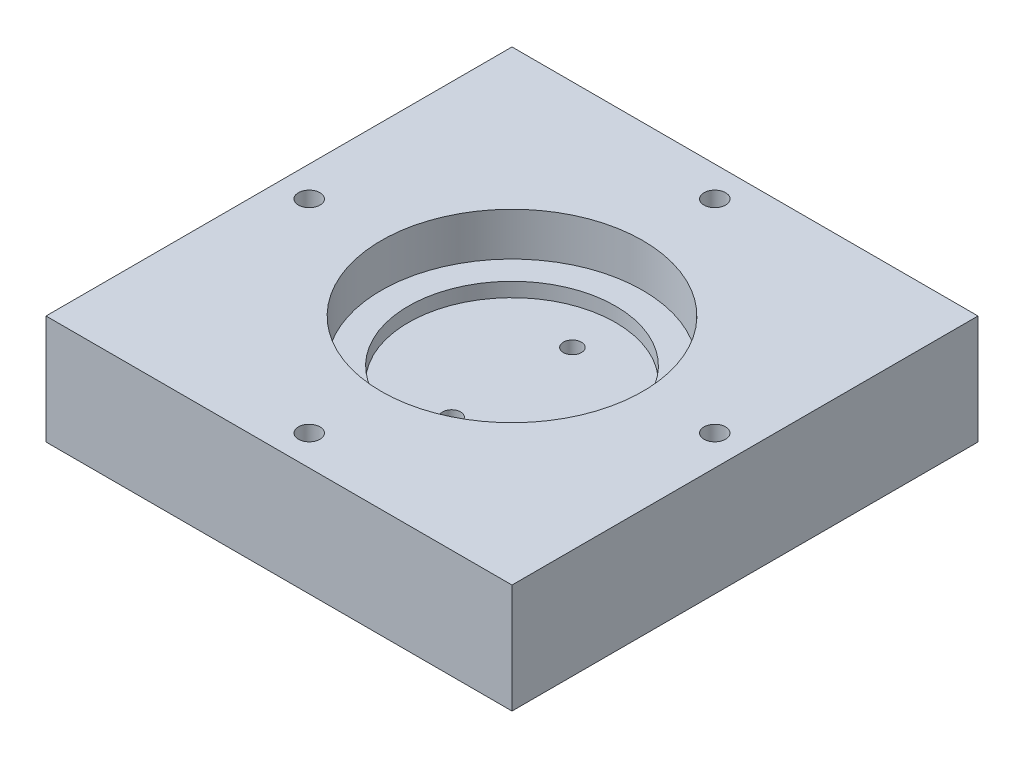
SolidWorks part; units mm, degrees
ref_plane "Front Plane" through (0, 0, 0) normal (0, 0, 1) x (1, 0, 0)
ref_plane "Top Plane" through (0, 0, 0) normal (0, 1, 0) x (1, 0, 0)
ref_plane "Right Plane" through (0, 0, 0) normal (1, 0, 0) x (0, 0, -1)
sketch "Sketch1" plane through (0, 0, 0) normal (0, 1, 0) x (1, 0, 0)
  circle A0 centre (0, 0) radius 11.5 construction
  circle A1 centre (0, 0) radius 7 construction
  circle A2 centre (0, 7) radius 1.05
  circle A3 centre (0, -7) radius 1.05
  circle A6 centre (0, 0) radius 27
  dimension "D1" = 23
  dimension "D2" = 2.1
  dimension "D3" = 14
  dimension "D4" = 54
extrude "Boss-Extrude1" add sketch "Sketch1" along normal blind 3
sketch "Sketch2" plane through (0, 3, 0) normal (0, 1, 0) x (1, 0, 0)
  circle A0 centre (0, 0) radius 12
  circle A1 centre (0, 0) radius 27
  dimension "D1" = 24
extrude "Boss-Extrude2" add sketch "Sketch2" along normal blind 1.65
sketch "Sketch3" plane through (0, 4.65, 0) normal (0, 1, 0) x (1, 0, 0)
  line L0 (-1.65, 0) -> (1.65, 0) construction
  line L1 (-26.971, 1.25) -> (-15.0983, 1.25) construction
  line L5 (-26.971, -1.25) -> (-15.0983, -1.25) construction
  arc A0 (-26.971, -1.25) -> (-26.971, 1.25) centre (0, 0) ccw construction
  circle A2 centre (0, 0) radius 27 construction
  arc A4 (-15.0983, -1.25) -> (-15.0983, 1.25) centre (0, 0) ccw construction
  circle A6 centre (0, 0) radius 15.15
  circle A7 centre (0, 0) radius 27
  dimension "D3" = 15.15
  dimension "D4" = 54
  dimension "D5" = 30.3
  dimension "D1" = 2.5
  dimension "D2" = 1.25
extrude "Boss-Extrude3" add sketch "Sketch3" along normal blind 5
fillet "Fillet1" [suppressed] radius 2.5
sketch "Sketch4" plane through (0, 0, 0) normal (0, -1, 0) x (1, 0, 0)
  circle A0 centre (0, -7) radius 1.875
  circle A1 centre (0, 7) radius 1.875
  circle A2 centre (0, 0) radius 27
  dimension "D1" = 3.75
  dimension "D2" = 3.75
extrude "Boss-Extrude4" add sketch "Sketch4" along normal blind 3
sketch "Sketch5" plane through (0, 9.65, 0) normal (0, 1, 0) x (1, 0, 0)
  line L5 (0, -1.65) -> (0, 1.65) construction
  line L6 (-0.75, 27.9703) -> (0.75, 27.9703)
  line L7 (-0.75, 27.9703) -> (-0.75, 24)
  line L8 (-0.75, 24) -> (0.75, 24)
  line L9 (0.75, 27.9703) -> (0.75, 24)
  circle A0 centre (0, 0) radius 27 construction
  point P4 (0, 27.9703)
  dimension "D2" = 3
  dimension "D1" = 1.5
extrude "Cut-Extrude1" [suppressed] cut sketch "Sketch5" against normal through all
pattern_circular "CirPattern1" [suppressed] count 8 over 360
sketch "Sketch6" plane through (0, 9.65, 0) normal (0, 1, 0) x (1, 0, 0)
  line L0 (0, -6.9575) -> (0, 6.9575) construction
  circle A0 centre (0, 23.5) radius 1.25
  dimension "D2" = 2.5
  dimension "D1" = 23.5
extrude "Cut-Extrude2" cut sketch "Sketch6" against normal through all
pattern_circular "CirPattern2" count 4 over 360 about axis through (0, 0, 0) along (0, 1, 0) of "Cut-Extrude2"
sketch "Sketch7" plane through (0, 0, 0) normal (0, 1, 0) x (1, 0, 0)
  line L1 (-27, 27) -> (27, 27)
  line L2 (-27, 27) -> (-27, -27)
  line L3 (-27, -27) -> (27, -27)
  line L4 (27, 27) -> (27, -27)
  circle A0 centre (0, 0) radius 27
extrude "Boss-Extrude5" add sketch "Sketch7" along normal up to surface and the other way up to surface contours A0 L1 L2 | A0 L4 L1 | A0 L3 L4 | A0 L2 L3 up to face at (-22.25, 9.65, 0) other way up to face at (-22.25, -3, 0)
